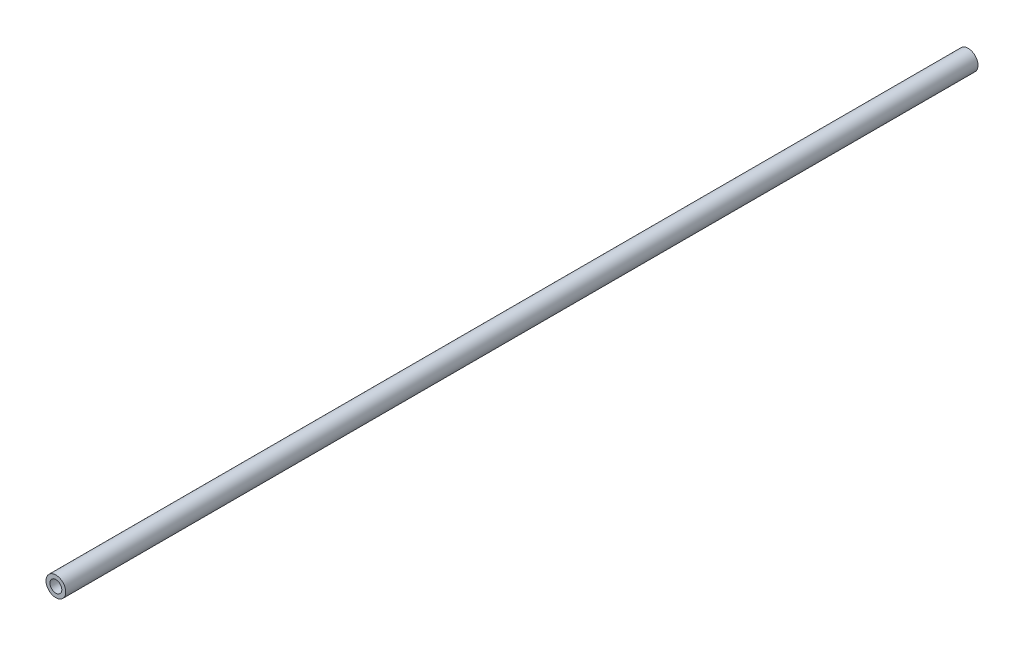
SolidWorks part; units mm, degrees
ref_plane "前视基准面" through (0, 0, 0) normal (0, 0, 1) x (1, 0, 0)
ref_plane "上视基准面" through (0, 0, 0) normal (0, 1, 0) x (1, 0, 0)
ref_plane "右视基准面" through (0, 0, 0) normal (1, 0, 0) x (0, 0, -1)
sketch "草图1" plane through (0, 0, 0) normal (0, 0, 1) x (1, 0, 0)
  circle A0 centre (0, 0) radius 3
  circle A1 centre (0, 0) radius 5
extrude "凸台-拉伸1" add sketch "草图1" along normal blind 462.5
equation "\"462.5.00mm\"=10"
